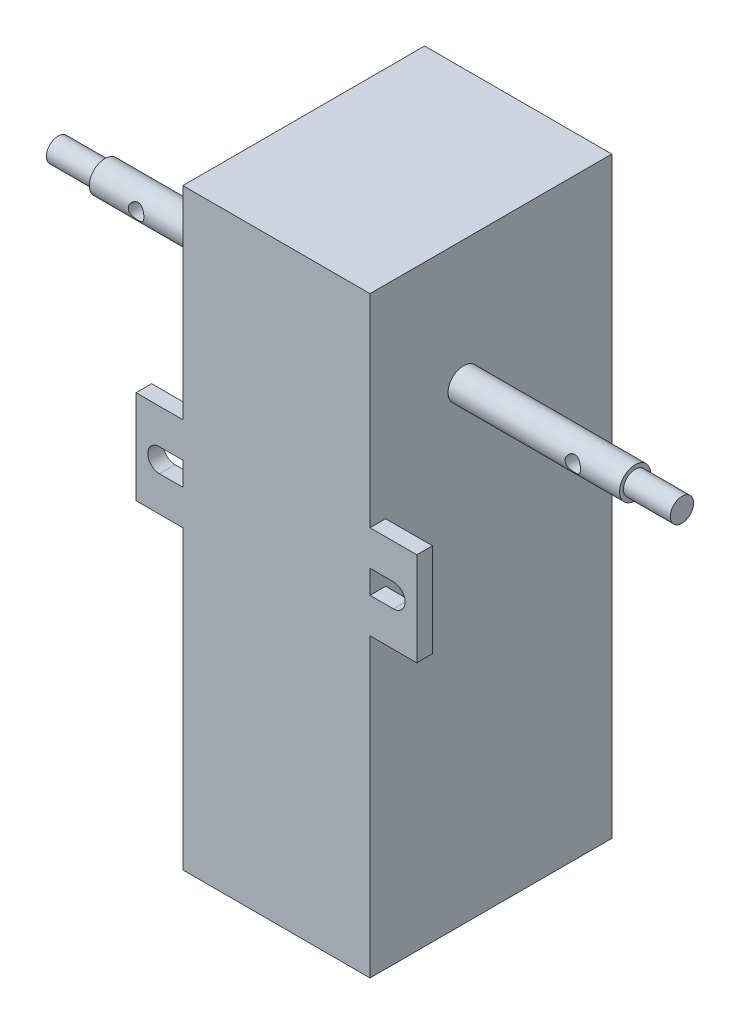
SolidWorks part; units mm, degrees
ref_plane "Front Plane" through (0, 0, 0) normal (0, 0, 1) x (1, 0, 0)
ref_plane "Top Plane" through (0, 0, 0) normal (0, 1, 0) x (1, 0, 0)
ref_plane "Right Plane" through (0, 0, 0) normal (1, 0, 0) x (0, 0, -1)
sketch "Sketch1" plane through (0, 0, 0) normal (0, 1, 0) x (1, 0, 0)
  line L1 (-12, -15.5) -> (12, -15.5)
  line L2 (-12, -15.5) -> (-12, 15.5)
  line L3 (-12, 15.5) -> (12, 15.5)
  line L4 (12, -15.5) -> (12, 15.5)
  line L5 (-12, -15.5) -> (12, 15.5) construction
  line L6 (-12, 15.5) -> (12, -15.5) construction
  point P0 (0, 0)
  dimension "D1" = 24
  dimension "D2" = 31
extrude "Boss-Extrude1" add sketch "Sketch1" along normal blind 76
sketch "Sketch2" plane through (12, 0, 0) normal (1, 0, 0) x (0, 0, -1)
  line L0 (-15.5, 76) -> (-15.5, 0) construction
  line L1 (-15.5, 76) -> (15.5, 76) construction
  circle A0 centre (-3.5, 60) radius 2
  dimension "D3" = 4
  dimension "D1" = 12
  dimension "D2" = 16
extrude "Boss-Extrude2" add sketch "Sketch2" along normal blind 28 and the other way blind 52
sketch "Sketch7" plane through (-40, 0, 0) normal (-1, 0, 0) x (0, 0, 1)
  circle A2 centre (3.5, 60) radius 1.5
  circle A3 centre (3.5, 60) radius 1.5
  circle A4 centre (3.5, 60) radius 2
  circle A5 centre (3.5, 60) radius 2
  dimension "D1" = 0.5
  dimension "D2" = 0
extrude "Cut-Extrude1" cut sketch "Sketch7" against normal blind 6
thread "Thread2" pitch 0.6 start angle 0, offset 0, length 6, pitch 0.6, diameter 3
ref_plane "Plane2" through (-40, 60, 2) normal (0, -1, 0) x (0, 0, -1)
sketch "Thread Profile2" plane through (-40, 60, 2) normal (0, -1, 0) x (0, 0, -1)
  line L0 (0, 0) -> (0, 0.6) construction
  line L11 (0, 0) -> (0, 0.525)
  line L12 (0, 0.525) -> (-0.3248, 0.3375)
  line L13 (-0.3248, 0.3375) -> (-0.3248, 0.1875)
  line L15 (-0.3248, 0.1875) -> (0, 0)
  line L17 (-0.3248, 0.2625) -> (0, 0.2625) construction
  point P2 (0, 0)
  dimension "Pitch" = 0.6
  dimension "Profile_Angle" = 60
  dimension "Profile_Land" = 0.15
  dimension "Profile_Height" = 0.3248
sketch "Sketch17" plane through (0, 0, 0) normal (0, 0, 1) x (1, 0, 0)
  line L0 (-12, 60) -> (-40, 60) construction
  line L1 (-12, 62) -> (-12, 58) construction
  line L2 (-40, 61.5) -> (-40, 58.5) construction
  circle A0 centre (-28, 60) radius 1
  dimension "D1" = 2
  dimension "D2" = 12
extrude "Cut-Extrude3" cut sketch "Sketch17" along normal through all
mirror "Mirror7" about plane through (0, 0, 0) normal (1, 0, 0) of "Cut-Extrude1"
sketch "Sketch18" plane through (12, 0, 0) normal (1, 0, 0) x (0, 0, -1)
  line L0 (-15.5, 76) -> (-15.5, 0) construction
  line L1 (-15.5, 50) -> (-13.5, 50)
  line L2 (-15.5, 50) -> (-15.5, 38)
  line L3 (-15.5, 38) -> (-13.5, 38)
  line L4 (-13.5, 50) -> (-13.5, 38)
  point P6 (-15.5, 44)
  point P7 (-3.5, 60)
  dimension "D1" = 12
  dimension "D2" = 2
  dimension "D3" = 16
extrude "Boss-Extrude3" add sketch "Sketch18" along normal blind 6
sketch "Sketch19" plane through (0, 0, 15.5) normal (0, 0, 1) x (1, 0, 0)
  line L1 (12, 45.5) -> (15, 45.5)
  line L2 (12, 45.5) -> (12, 42.5)
  line L3 (12, 42.5) -> (15, 42.5)
  line L4 (15, 45.5) -> (15, 42.5) construction
  line L5 (12, 38) -> (12, 0) construction
  line L6 (18, 50) -> (18, 38) construction
  arc A0 (15, 45.5) -> (15, 42.5) centre (15, 44) cw
  point P8 (18, 44)
  dimension "D1" = 3
  dimension "D2" = 3
extrude "Cut-Extrude4" cut sketch "Sketch19" against normal up to next contours L1 A0 L3 L2
mirror "Mirror8" about plane through (0, 0, 0) normal (1, 0, 0) of "Boss-Extrude3", "Cut-Extrude4"
mirror "Mirror9" about plane through (0, 0, 0) normal (1, 0, 0) of "Cut-Extrude3"
sketch "Sketch20" plane through (0, 0, 15.5) normal (0, 0, 1) x (1, 0, 0)
  point P0 (-15, 44)
  point P1 (15, 44)
